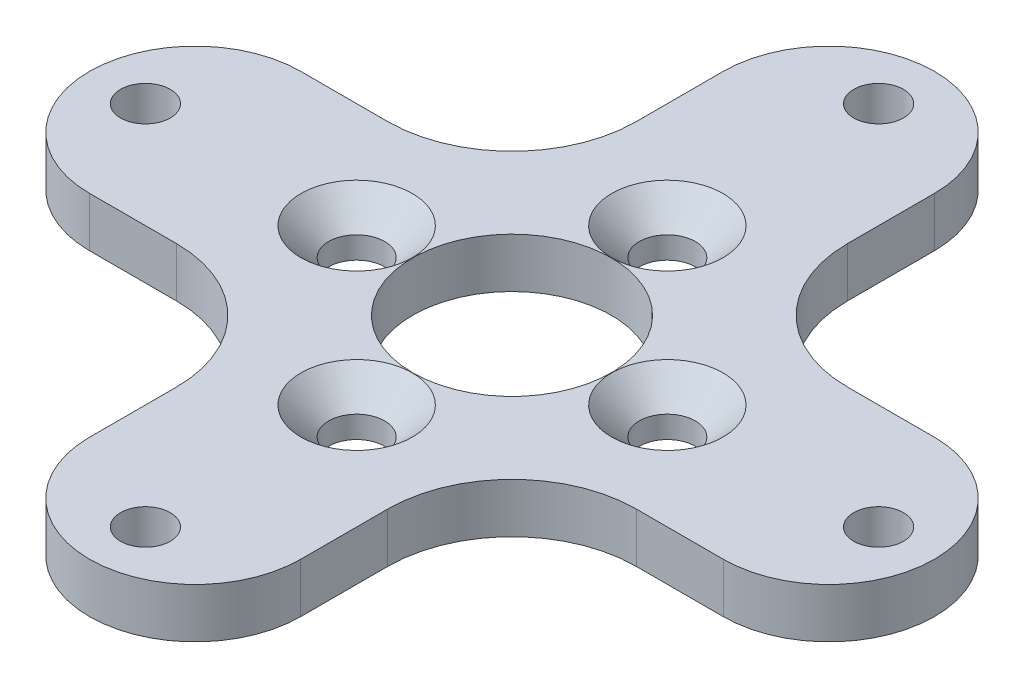
SolidWorks part; units mm, degrees
ref_plane "Plano frontal" through (0, 0, 0) normal (0, 0, 1) x (1, 0, 0)
ref_plane "Plano superior" through (0, 0, 0) normal (0, 1, 0) x (1, 0, 0)
ref_plane "Plano direito" through (0, 0, 0) normal (1, 0, 0) x (0, 0, -1)
sketch "Esboço1" plane through (0, 0, 0) normal (0, 1, 0) x (1, 0, 0)
  line L0 (0, 25.5) -> (0, -25.5) construction
  line L1 (8.5, 25.5) -> (8.5, -25.5)
  line L2 (-8.5, 25.5) -> (-8.5, -25.5)
  line L3 (-25.5, 0) -> (25.5, 0) construction
  line L4 (-25.5, 8.5) -> (25.5, 8.5)
  line L5 (-25.5, -8.5) -> (25.5, -8.5)
  arc A2 (8.5, 25.5) -> (-8.5, 25.5) centre (0, 25.5) ccw
  arc A3 (-8.5, -25.5) -> (8.5, -25.5) centre (0, -25.5) ccw
  arc A4 (-25.5, 8.5) -> (-25.5, -8.5) centre (-25.5, 0) ccw
  arc A5 (25.5, -8.5) -> (25.5, 8.5) centre (25.5, 0) ccw
  point P2 (0, 0)
  point P3 (0, 0)
  point P15 (0, 34)
  dimension "D1" = 17
  dimension "D2" = 17
  dimension "D3" = 34
extrude "Ressalto-extrusão1" add sketch "Esboço1" along normal mid plane 4 contours L4 A4 L5 L2 | L1 A2 L2 L4 | L2 L5 L1 L4 | L5 A5 L4 L1 | L2 A3 L1 L5
fillet "Filete1" radius 10 4 edges at (-8.5, 0, -8.5) (8.5, 0, -8.5) (8.5, 0, 8.5) (-8.5, 0, 8.5)
sketch "Esboço3" plane through (0, 2, 0) normal (0, 1, 0) x (1, 0, 0)
  line L0 (0, 49.8948) -> (0, -46.9321) construction
  line L1 (-53.9078, 0) -> (54.9002, 0) construction
  circle A0 centre (0, 0) radius 8
  circle A2 centre (0, 29.5) radius 2
  arc A3 (8.5, 25.5) -> (-8.5, 25.5) centre (0, 25.5) ccw construction
  point P14 (0, 34)
  dimension "D1" = 16
  dimension "D2" = 4
  dimension "D3" = 4.5
extrude "Corte-extrusão1" cut sketch "Esboço3" against normal through all
pattern_circular "PadrãoCircular1" count 4 over 360 about axis through (0, 0, 0) along (0, 1, 0) of "Corte-extrusão1"
hole_wizard "Escareado para SFHCS M41" positions "Esboço5" profile "Esboço6" countersink size "M4" standard "Ansi Metric" end condition through all
sketch "Esboço5" plane through (0, 2, 0) normal (0, 1, 0) x (1, 0, 0)
  point P0 (-12.5, 0)
  point P2 (0, 12.5)
  point P4 (12.5, 0)
  point P6 (0, -12.5)
  dimension "D1" = 25
  dimension "D2" = 12.5
  dimension "D3" = 25
  dimension "D4" = 12.5
sketch "Esboço6" plane through (-12.5, 2, 0) normal (1, 0, 0) x (0, 0, 1)
  line L0 (0, 0) -> (0, 4)
  line L1 (0, 4) -> (2.25, 4)
  line L2 (2.25, 4) -> (2.25, 2.23)
  line L3 (2.25, 2.23) -> (4.48, 0)
  line L5 (4.48, 0) -> (0, 0)
  line L6 (-2.25, 2.23) -> (-4.48, 0) construction
  line L11 (0, -6.35) -> (0, 107.95) construction
  dimension "Thru Hole Dia." = 4.5
  dimension "Thru Hole Depth" = 4
  dimension "Near C'Sink Dia." = 8.96
  dimension "Near C'Sink Angle" = 90
